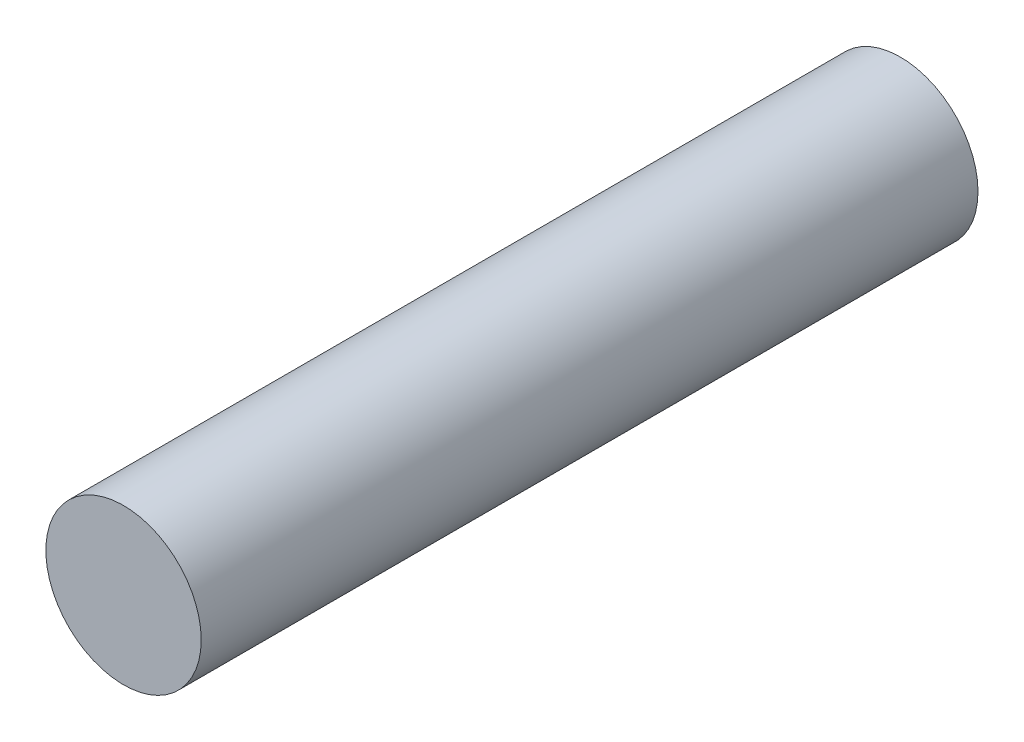
SolidWorks part; units mm, degrees
ref_plane "Front Plane" through (0, 0, 0) normal (1, 0, 0) x (0, 1, 0)
ref_plane "Top Plane" through (0, 0, 0) normal (0, 0, 1) x (0, 1, 0)
ref_plane "Right Plane" through (0, 0, 0) normal (0, 1, 0) x (-1, 0, 0)
sketch "Sketch1" plane through (0, 0, 0) normal (0, 0, 1) x (0, 1, 0)
  circle A0 centre (0, 0) radius 1
  dimension "D1" = 2
extrude "Boss-Extrude1" add sketch "Sketch1" along normal blind 10 contours A0
